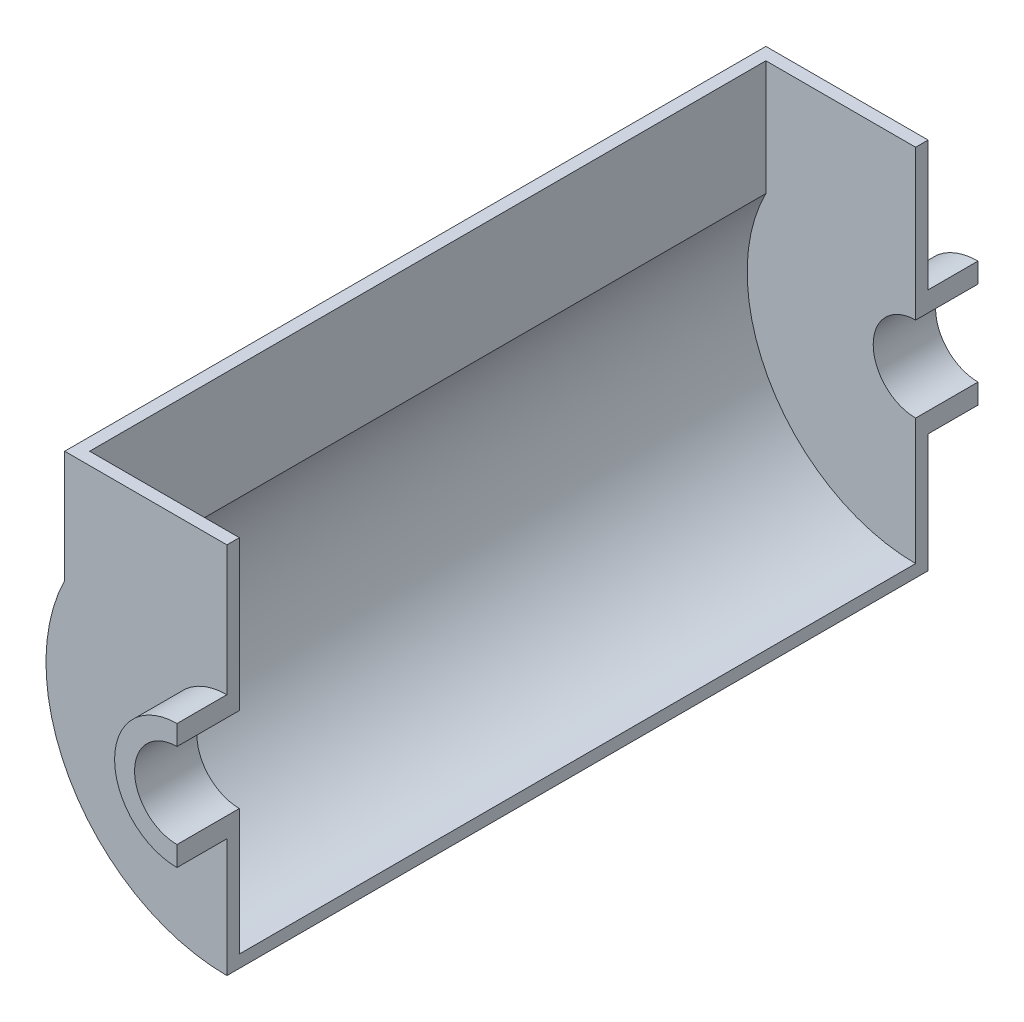
SolidWorks part; units mm, degrees
ref_plane "Front Plane" through (0, 0, 0) normal (0, 0, 1) x (1, 0, 0)
ref_plane "Top Plane" through (0, 0, 0) normal (0, 1, 0) x (1, 0, 0)
ref_plane "Right Plane" through (0, 0, 0) normal (1, 0, 0) x (0, 0, -1)
sketch "Sketch1" plane through (0, 0, 0) normal (0, 0, 1) x (1, 0, 0)
  line L0 (0, 25) -> (0, 17) construction
  line L1 (0, -17) -> (0, -25) construction
  line L2 (0, 25) -> (0, 17)
  line L3 (0, -17) -> (0, -25)
  arc A0 (0, 25) -> (0, -25) centre (0, 0) ccw
  arc A1 (0, 17) -> (0, -17) centre (0, 0) ccw
  dimension "D1" = 50
  dimension "D2" = 34
extrude "Boss-Extrude1" add sketch "Sketch1" along normal blind 20 and the other way blind 5
sketch "Sketch2" plane through (0, 0, 0) normal (0, 0, 1) x (1, 0, 0)
  line L0 (0, 25) -> (0, 77)
  line L1 (0, 77) -> (-65, 77)
  line L2 (-65, 77) -> (-65, 32.1131)
  line L3 (0, -25) -> (0, -72.5)
  arc A0 (0, 25) -> (0, -25) centre (0, 0) ccw construction
  arc A1 (0, 25) -> (0, -25) centre (0, 0) ccw
  arc A2 (-65, 32.1131) -> (0, -72.5) centre (0, 0) ccw
  dimension "D3" = 72.5
  dimension "D1" = 52
  dimension "D2" = 65
extrude "Boss-Extrude2" add sketch "Sketch2" against normal blind 5
ref_plane "Plane1" through (0, 0, -140.5) normal (0, 0, 1) x (1, 0, 0)
mirror "Mirror3" about plane through (0, 0, -140.5) normal (0, 0, 1) of bodies 102
sketch "Sketch3" plane through (0, 0, -5) normal (0, 0, -1) x (-1, 0, 0)
  line L0 (65, 77) -> (65, 32.1131) construction
  line L1 (65, 77) -> (65, 32.1131)
  line L2 (60, 77) -> (60, 30.9233)
  line L3 (65, 77) -> (60, 77)
  line L4 (0, -72.5) -> (0, -67.5)
  arc A0 (0, -72.5) -> (65, 32.1131) centre (0, 0) ccw construction
  arc A1 (0, -72.5) -> (65, 32.1131) centre (0, 0) ccw
  arc A2 (0, -67.5) -> (60, 30.9233) centre (0, 0) ccw
  dimension "D1" = 5
extrude "Boss-Extrude3" add sketch "Sketch3" along normal up to surface (271 mm away)
